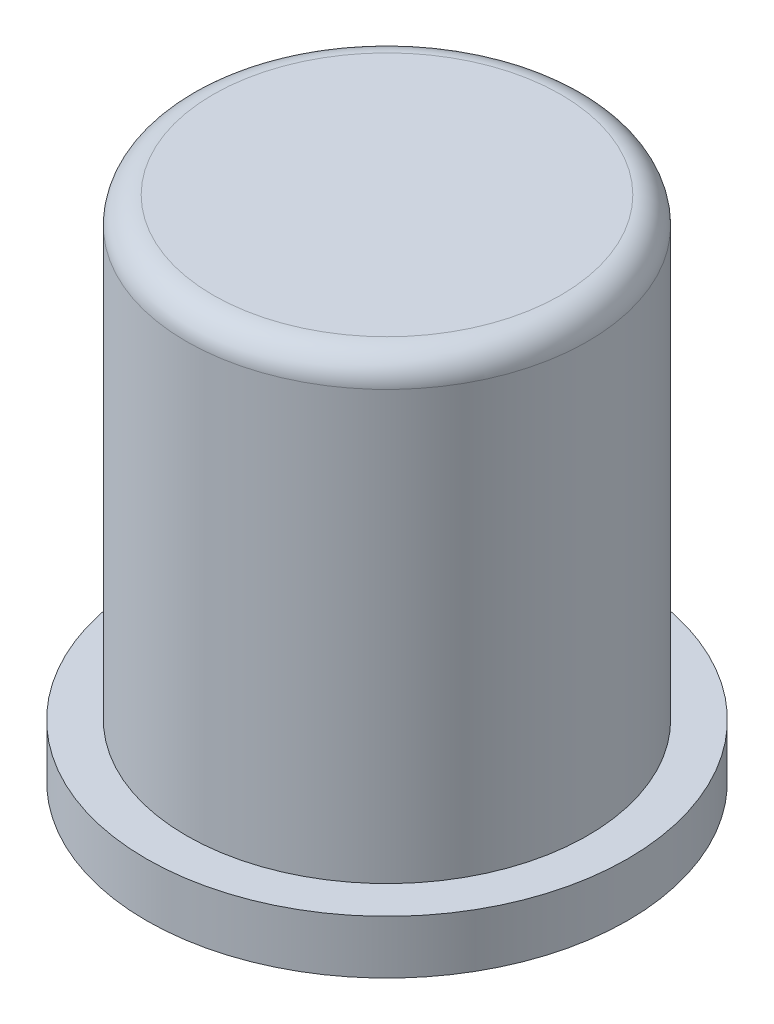
SolidWorks part; units mm, degrees
ref_plane "Alzado" through (0, 0, 0) normal (0, 0, 1) x (1, 0, 0)
ref_plane "Planta" through (0, 0, 0) normal (0, 1, 0) x (1, 0, 0)
ref_plane "Vista lateral" through (0, 0, 0) normal (1, 0, 0) x (0, 0, -1)
sketch "Croquis1" plane through (0, 0, 0) normal (0, 1, 0) x (1, 0, 0)
  circle A0 centre (0, 0) radius 4.5
extrude "Saliente-Extruir1" add sketch "Croquis1" along normal blind 9.5
sketch "Croquis2" plane through (0, 9.5, 0) normal (0, 1, 0) x (1, 0, 0)
  circle A0 centre (0, 0) radius 3.75
  circle A1 centre (0, 0) radius 4.5 construction
  circle A2 centre (0, 0) radius 4.5
extrude "Cortar-Extruir1" cut sketch "Croquis2" against normal blind 8.5
fillet "Redondeo1" radius 0.5 1 edges at (0, 9.5, 3.75)
